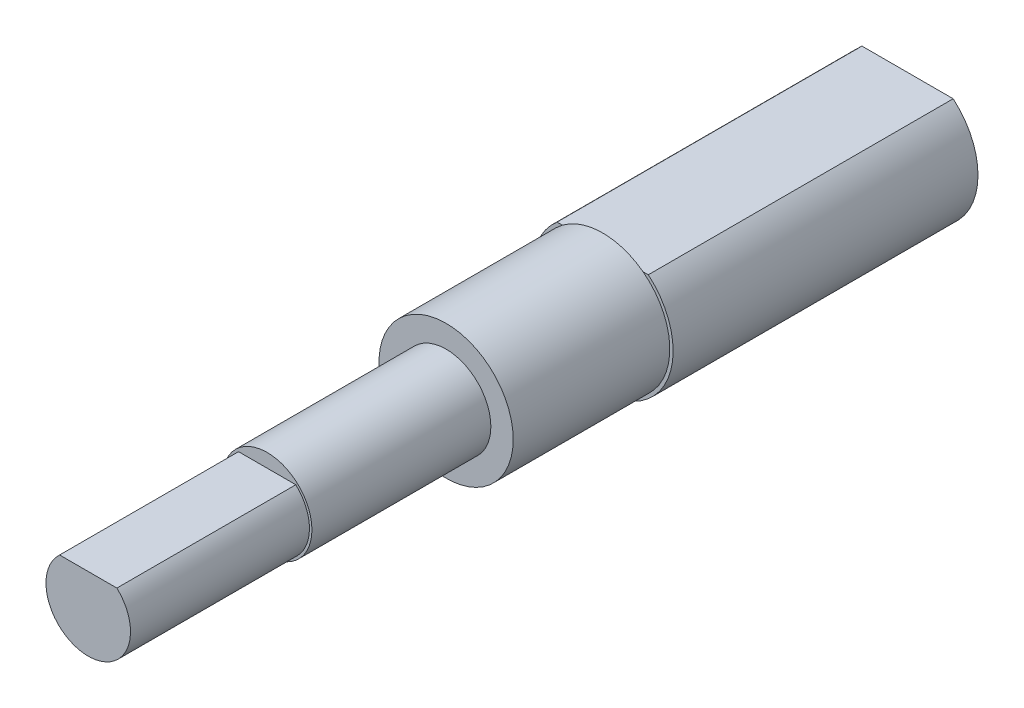
SolidWorks part; units mm, degrees
material "ASTM A36 Steel"
ref_plane "Front" through (0, 0, 0) normal (0, 0, 1) x (1, 0, 0)
ref_plane "Top" through (0, 0, 0) normal (0, 1, 0) x (1, 0, 0)
ref_plane "Right" through (0, 0, 0) normal (1, 0, 0) x (0, 0, -1)
sketch "Sketch1" plane through (0, 0, 0) normal (0, 0, 1) x (1, 0, 0)
  circle A0 centre (0, 0) radius 5
  dimension "D1" = 10
extrude "Boss-Extrude1" add sketch "Sketch1" along normal blind 21.6375
sketch "Sketch2" plane through (0, 0, 21.6375) normal (0, 0, 1) x (1, 0, 0)
  circle A0 centre (0, 0) radius 4.7625
  dimension "D1" = 9.525
extrude "Boss-Extrude2" add sketch "Sketch2" along normal blind 11.1125
sketch "Sketch3" plane through (0, 0, 32.75) normal (0, 0, 1) x (1, 0, 0)
  circle A0 centre (0, 0) radius 3.175
  dimension "D1" = 6.35
extrude "Boss-Extrude3" add sketch "Sketch3" along normal blind 12.7
sketch "Sketch4" plane through (0, 0, 0) normal (0, 0, -1) x (-1, 0, 0)
  line L0 (0, 0) -> (0, 5) construction
  line L2 (12.7, 3.8094) -> (-12.7, 3.8094)
  line L3 (12.7, 3.8094) -> (12.7, 6.1906)
  line L4 (12.7, 6.1906) -> (-12.7, 6.1906)
  line L5 (-12.7, 3.8094) -> (-12.7, 6.1906)
  line L6 (12.7, 3.8094) -> (-12.7, 6.1906) construction
  line L7 (12.7, 6.1906) -> (-12.7, 3.8094) construction
  circle A0 centre (0, 0) radius 5 construction
  dimension "D1" = 2.3813
  dimension "D2" = 25.4
extrude "Cut-Extrude1" cut sketch "Sketch4" against normal up to surface (21.6375 mm away) up to face at (4.7625, 0, 21.6375)
sketch "Sketch5" plane through (0, 0, 45.45) normal (0, 0, 1) x (1, 0, 0)
  line L0 (0, 0) -> (0, 3.175) construction
  line L2 (12.7, 2.3813) -> (-12.7, 2.3812)
  line L3 (12.7, 2.3813) -> (12.7, 3.9688)
  line L4 (12.7, 3.9688) -> (-12.7, 3.9687)
  line L5 (-12.7, 2.3812) -> (-12.7, 3.9687)
  line L6 (12.7, 2.3813) -> (-12.7, 3.9687) construction
  line L7 (12.7, 3.9688) -> (-12.7, 2.3812) construction
  circle A0 centre (0, 0) radius 3.175 construction
  dimension "D1" = 1.5875
  dimension "D2" = 25.4
sketch "Sketch6" plane through (0, 0, 45.45) normal (0, 0, 1) x (1, 0, 0)
  circle A0 centre (0, 0) radius 3
  dimension "D1" = 6
extrude "Boss-Extrude4" add sketch "Sketch6" along normal blind 12.7
sketch "Sketch7" plane through (0, 0, 58.15) normal (0, 0, 1) x (1, 0, 0)
  line L0 (0, 0) -> (0, 3) construction
  line L2 (12.6863, 2.2063) -> (-12.6863, 2.2062)
  line L3 (12.6863, 2.2063) -> (12.6863, 3.7938)
  line L4 (12.6863, 3.7938) -> (-12.6863, 3.7937)
  line L5 (-12.6863, 2.2062) -> (-12.6863, 3.7937)
  line L6 (12.6863, 2.2063) -> (-12.6863, 3.7937) construction
  line L7 (12.6863, 3.7938) -> (-12.6863, 2.2062) construction
  circle A0 centre (0, 0) radius 3 construction
  dimension "D1" = 1.5875
  dimension "D2" = 25.3725
extrude "Cut-Extrude3" cut sketch "Sketch7" against normal up to surface (12.7 mm away) up to face at (3, 0, 45.45)
